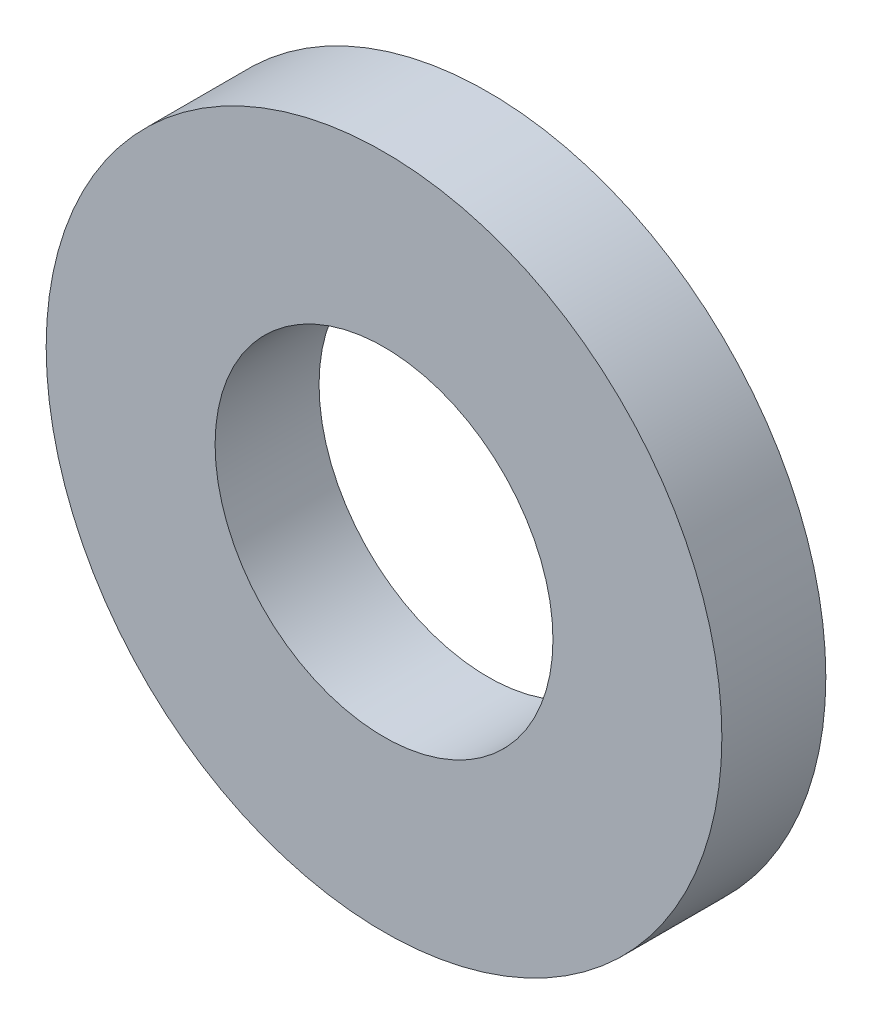
SolidWorks part; units mm, degrees
ref_plane "Front Plane" through (0, 0, 0) normal (0, 0, 1) x (1, 0, 0)
ref_plane "Top Plane" through (0, 0, 0) normal (0, 1, 0) x (1, 0, 0)
ref_plane "Right Plane" through (0, 0, 0) normal (1, 0, 0) x (0, 0, -1)
sketch "Эскиз1" plane through (0, 0, 0) normal (0, 0, 1) x (1, 0, 0)
  circle A0 centre (0, 0) radius 32.5
  circle A1 centre (0, 0) radius 16.25
extrude "Бобышка-Вытянуть1" add sketch "Эскиз1" along normal blind 10
